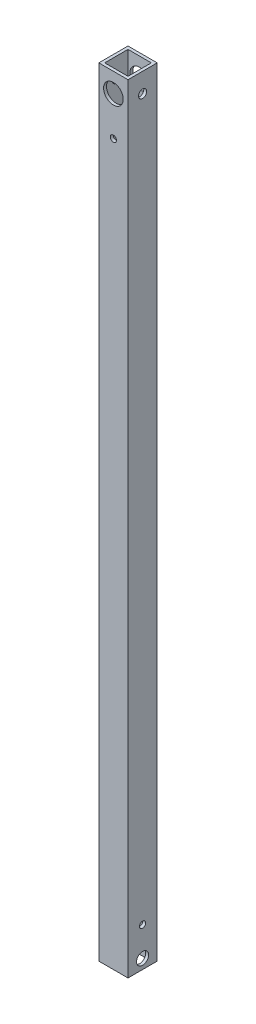
SolidWorks part; units mm, degrees
material "1060 合金"
ref_plane "正面" through (0, 0, 0) normal (0, 0, 1) x (1, 0, 0)
ref_plane "平面" through (0, 0, 0) normal (0, 1, 0) x (1, 0, 0)
ref_plane "右側面" through (0, 0, 0) normal (1, 0, 0) x (0, 0, -1)
sketch "ｽｹｯﾁ1" plane through (0, 0, 0) normal (0, 1, 0) x (1, 0, 0)
  line L1 (-7.5, 7.5) -> (7.5, 7.5)
  line L2 (-7.5, 7.5) -> (-7.5, -7.5)
  line L3 (-7.5, -7.5) -> (7.5, -7.5)
  line L4 (7.5, 7.5) -> (7.5, -7.5)
  line L5 (-7.5, 7.5) -> (7.5, -7.5) construction
  line L6 (-7.5, -7.5) -> (7.5, 7.5) construction
  point P0 (0, 0)
  dimension "D1" = 15
extrude "押し出し-薄板1" add sketch "ｽｹｯﾁ1" along normal blind 400 thin
sketch "ｽｹｯﾁ2" plane through (0, 0, 7.5) normal (0, 0, 1) x (1, 0, 0)
  line L0 (0, 0) -> (0, 400) construction
  line L1 (-7.5, 400) -> (7.5, 400) construction
  circle A0 centre (0, 390) radius 5.05
  circle A1 centre (0, 370) radius 1.6
  dimension "D1" = 10.1
  dimension "D2" = 3.2
  dimension "D3" = 20
  dimension "D4" = 10
extrude "ｶｯﾄ - 押し出し1" cut sketch "ｽｹｯﾁ2" against normal through all
sketch "ｽｹｯﾁ3" plane through (7.5, 0, 0) normal (1, 0, 0) x (0, 0, -1)
  line L0 (0, 400) -> (0, 390) construction
  line L1 (-7.5, 400) -> (7.5, 400) construction
  circle A0 centre (0, 390) radius 2.1
  dimension "D1" = 4.2
  dimension "D2" = 10
extrude "ｶｯﾄ - 押し出し2" cut sketch "ｽｹｯﾁ3" against normal through all
sketch "ｽｹｯﾁ4" plane through (7.5, 0, 0) normal (1, 0, 0) x (0, 0, -1)
  line L0 (0, 0) -> (0, 5) construction
  circle A0 centre (0, 5) radius 3.1
  dimension "D1" = 6.2
  dimension "D2" = 5
extrude "ｶｯﾄ - 押し出し3" cut sketch "ｽｹｯﾁ4" against normal through all
sketch "ｽｹｯﾁ5" plane through (7.5, 0, 0) normal (1, 0, 0) x (0, 0, -1)
  line L0 (0, 5) -> (0, 20) construction
  circle A0 centre (0, 5) radius 3.1 construction
  circle A1 centre (0, 5) radius 3.1
  circle A2 centre (0, 20) radius 1.6
  dimension "D2" = 3.2
  dimension "D1" = 15
extrude "ｶｯﾄ - 押し出し4" cut sketch "ｽｹｯﾁ5" against normal through all
